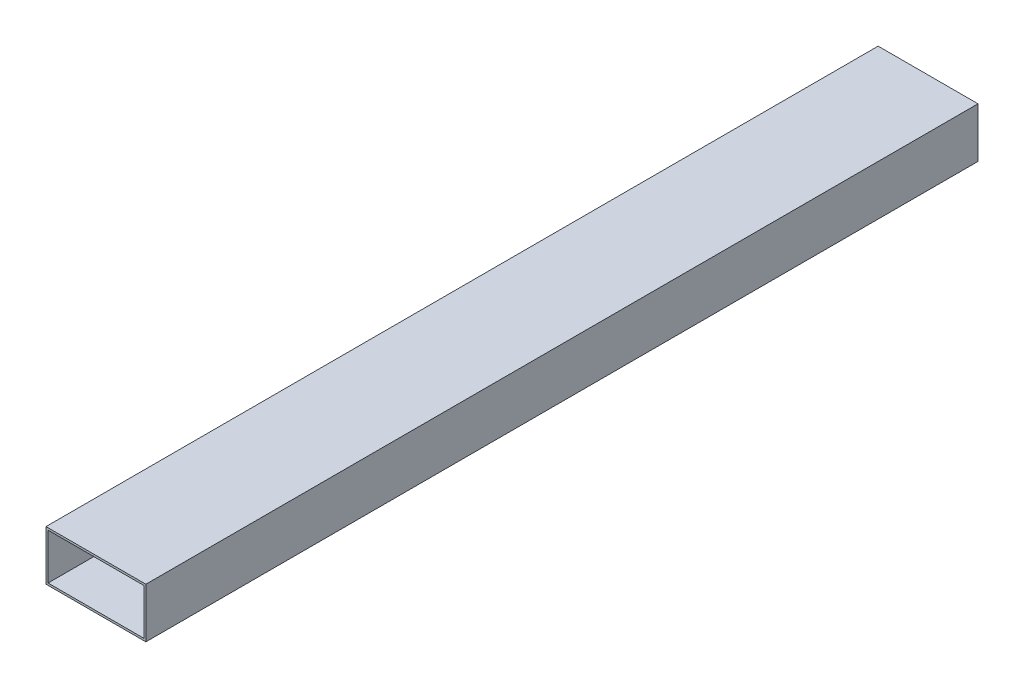
SolidWorks part; units mm, degrees
ref_plane "Front Plane" through (0, 0, 0) normal (0, 0, 1) x (1, 0, 0)
ref_plane "Top Plane" through (0, 0, 0) normal (0, 1, 0) x (1, 0, 0)
ref_plane "Right Plane" through (0, 0, 0) normal (1, 0, 0) x (0, 0, -1)
sketch "Sketch1" plane through (0, 0, 0) normal (0, 0, 1) x (1, 0, 0)
  line L0 (-23, 11) -> (23, 11)
  line L1 (-24, -12) -> (24, -12)
  line L2 (-24, -12) -> (-24, 12)
  line L3 (-24, 12) -> (24, 12)
  line L4 (24, -12) -> (24, 12)
  line L5 (-24, -12) -> (24, 12) construction
  line L6 (-24, 12) -> (24, -12) construction
  line L7 (23, -11) -> (23, 11)
  line L8 (-23, -11) -> (23, -11)
  line L9 (-23, -11) -> (-23, 11)
  point P0 (0, 0)
  dimension "D1" = 48
  dimension "D2" = 24
  dimension "D3" = 1
extrude "Boss-Extrude1" add sketch "Sketch1" along normal blind 400
